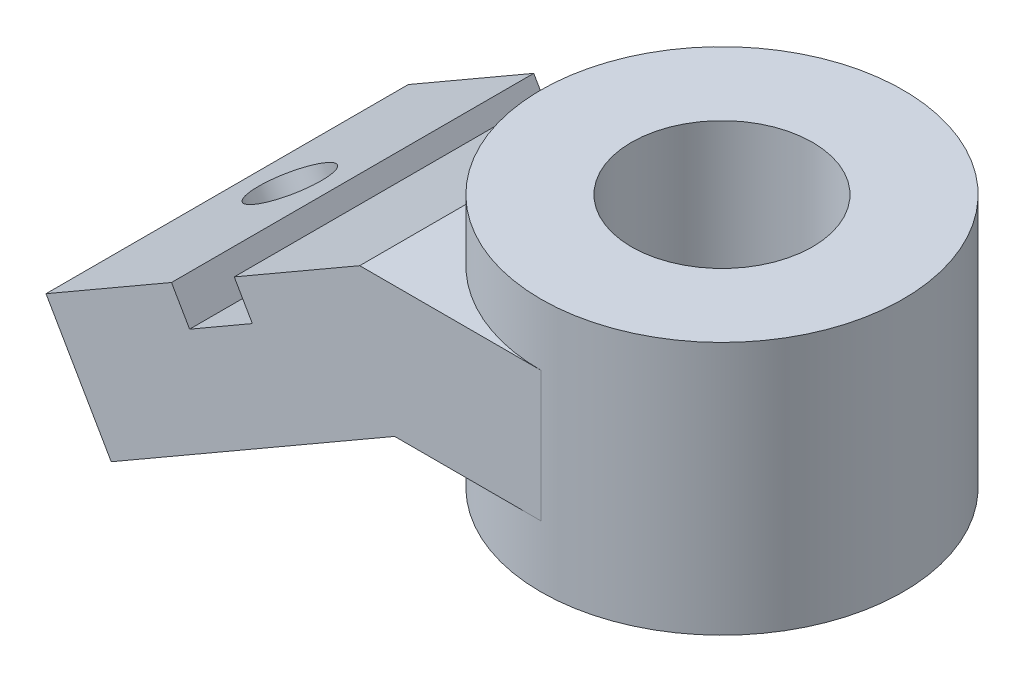
SolidWorks part; units mm, degrees
ref_plane "Front Plane" through (0, 0, 0) normal (0, 0, 1) x (1, 0, 0)
ref_plane "Top Plane" through (0, 0, 0) normal (0, 1, 0) x (1, 0, 0)
ref_plane "Right Plane" through (0, 0, 0) normal (1, 0, 0) x (0, 0, -1)
sketch "Sketch1" plane through (0, 0, 0) normal (0, 0, 1) x (1, 0, 0)
  line L0 (0, 9) -> (0, -9)
  line L1 (0, -9) -> (-20.1769, -9)
  line L2 (-20.1769, -9) -> (-59.3013, -31.5885)
  line L3 (-59.3013, -31.5885) -> (-68.3013, -16)
  line L4 (-68.3013, -16) -> (-25, 9)
  line L5 (-25, 9) -> (0, 9)
  line L6 (0, 0) -> (25.9255, 0) construction
  dimension "D1" = 18
  dimension "D2" = 18
  dimension "D3" = 50
  dimension "D4" = 150
  dimension "D5" = 25
extrude "Boss-Extrude1" add sketch "Sketch1" along normal blind 50
sketch "Sketch3" plane through (0, 0, 0) normal (0, 1, 0) x (1, 0, 0)
  line L0 (0, -50) -> (0, 0) construction
  circle A0 centre (0, -25) radius 25
  dimension "D1" = 50
extrude "Boss-Extrude2" add sketch "Sketch3" along normal mid plane 35
hole_wizard "Hole1" positions "Sketch5" profile "Sketch6" legacy end condition up to next
sketch "Sketch5" plane through (0, 17.5, 0) normal (0, 1, 0) x (1, 0, 0)
  point P0 (0, -25)
sketch "Sketch6" plane through (0, 17.5, 25) normal (1, 0, 0) x (0, 0, 1)
  line L0 (0, 0) -> (0, 35)
  line L1 (0, 35) -> (12.5, 35)
  line L2 (12.5, 35) -> (12.5, 0)
  line L3 (12.5, 0) -> (0, 0)
  line L4 (0, 110) -> (0, -10) construction
  dimension "Diameter" = 25
  dimension "Depth" = 35
hole_wizard "Hole2" positions "Sketch7" profile "Sketch8" legacy end condition up to next
sketch "Sketch7" plane through (-10.1471, 17.5753, 0) normal (-0.5, 0.866, 0) x (0.866, 0.5, 0)
  line L0 (-67.1506, -50) -> (-67.1506, 0) construction
  line L2 (-17.1506, -50) -> (-67.1506, -50) construction
  point P0 (-57.1506, -25)
  dimension "D1" = 10
  dimension "D2" = 25
sketch "Sketch8" plane through (-59.641, -11, 25) normal (0, 0, 1) x (-0.866, -0.5, 0)
  line L0 (0, 0) -> (0, 18)
  line L1 (0, 18) -> (5, 18)
  line L2 (5, 18) -> (5, 0)
  line L3 (5, 0) -> (0, 0)
  line L4 (0, 110) -> (0, -10) construction
  dimension "Diameter" = 10
  dimension "Depth" = 18
sketch "Sketch9" plane through (0, 0, 50) normal (0, 0, 1) x (1, 0, 0)
  line L0 (-50.9808, -6) -> (-42.3205, -1)
  line L1 (-50.9808, -6) -> (-48.4808, -10.3301)
  line L2 (-42.3205, -1) -> (-39.8205, -5.3301)
  line L3 (-48.4808, -10.3301) -> (-39.8205, -5.3301)
  line L4 (-25, 9) -> (-68.3013, -16) construction
  line L5 (-68.3013, -16) -> (-59.3013, -31.5885) construction
  point P8 (-46.6506, -3.5)
  dimension "D1" = 5
  dimension "D2" = 10
  dimension "D3" = 25
extrude "Cut-Extrude1" cut sketch "Sketch9" against normal through all
